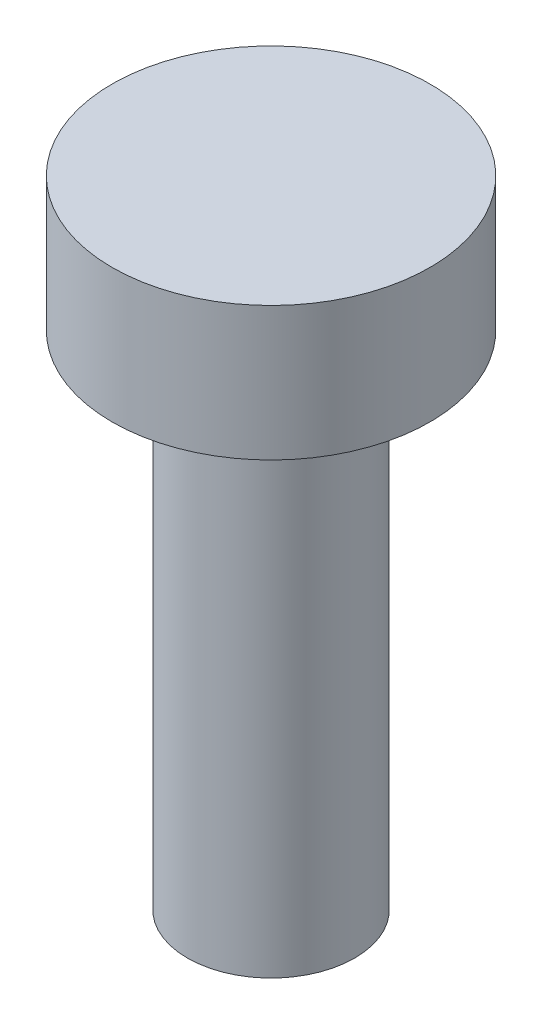
SolidWorks part; units mm, degrees
ref_plane "Front Plane" through (0, 0, 0) normal (0, 0, 1) x (1, 0, 0)
ref_plane "Top Plane" through (0, 0, 0) normal (0, 1, 0) x (1, 0, 0)
ref_plane "Right Plane" through (0, 0, 0) normal (1, 0, 0) x (0, 0, -1)
other "Configuration Table"
sketch "Sketch1" plane through (0, 0, 0) normal (0, 1, 0) x (1, 0, 0)
  circle A0 centre (0, 0) radius 1.9
  dimension "D1" = 3.8
extrude "Head" add sketch "Sketch1" along normal blind 1.6
sketch "Sketch2" plane through (0, 0, 0) normal (0, 1, 0) x (1, 0, 0)
  circle A0 centre (0, 0) radius 1
  dimension "D1" = 2
extrude "Shank" add sketch "Sketch2" along normal blind 6 from offset 6
equation "\"Jar_OD\"= 90  'ASSUMED - Part G fallback - jar outer diameter"
equation "\"Jar_H\"= 120  'ASSUMED - Part G fallback - jar height"
equation "\"Pump_L\"= 45  'ASSUMED - Part G fallback"
equation "\"Pump_W\"= 24  'ASSUMED - Part G fallback"
equation "\"Pump_H\"= 33  'ASSUMED - Part G fallback"
equation "\"Pump_Outlet_OD\"= 7.5  'ASSUMED - Part G fallback"
equation "\"Tube_OD\"= 8  'ASSUMED - Part G fallback"
equation "\"Tube_ID\"= 6  'ASSUMED - Part G fallback"
equation "\"TDS_Body_Dia\"= 12  'ASSUMED - Part G fallback"
equation "\"TDS_Wet_Len\"= 45  'ASSUMED - Part G fallback - length in water"
equation "\"DS_Tube_Dia\"= 6  'ASSUMED - Part G fallback"
equation "\"DS_Tube_Len\"= 50  'ASSUMED - Part G fallback"
equation "\"ORP_Body_Dia\"= 12  'ASSUMED - Part G fallback"
equation "\"ORP_Body_Len\"= 150  'ASSUMED - Part G fallback"
equation "\"ORP_Cap_Dia\"= 16  'ASSUMED - Part G fallback"
equation "\"Turb_W\"= 33  'ASSUMED - Part G fallback - head width"
equation "\"Turb_D\"= 28  'ASSUMED - Part G fallback - head depth"
equation "\"Turb_H\"= 30  'ASSUMED - Part G fallback - head height"
equation "\"Turb_Slot_W\"= 10  'ASSUMED - Part G fallback - slot width"
equation "\"Flow_L\"= 62  'ASSUMED - Part G fallback YF-S201"
equation "\"Flow_W\"= 36  'ASSUMED - Part G fallback"
equation "\"Flow_H\"= 35  'ASSUMED - Part G fallback"
equation "\"Thread_G12_OD\"= 20.955  'ASSUMED - Part G fallback thread G1/2 (major diameter)"
equation "\"Valve_L\"= 75  'ASSUMED - Part G fallback"
equation "\"Valve_W\"= 45  'ASSUMED - Part G fallback"
equation "\"Valve_H\"= 60  'ASSUMED - Part G fallback"
equation "\"Tee_L\"= 40  'ASSUMED - Part G fallback - overall length"
equation "\"Tee_Branch_L\"= 25  'ASSUMED - Part G fallback"
equation "\"Tee_OD\"= 12  'ASSUMED - Part G fallback"
equation "\"LED_Board_L\"= 20  'ASSUMED - Part G fallback"
equation "\"LED_Board_W\"= 20  'ASSUMED - Part G fallback - LED at centre"
equation "\"GUVA_L\"= 20  'ASSUMED - Part G fallback"
equation "\"GUVA_W\"= 12  'ASSUMED - Part G fallback - sensor at centre"
equation "\"Reed_L\"= 27  'ASSUMED - Part G fallback MC-38 half"
equation "\"Reed_W\"= 14  'ASSUMED - Part G fallback"
equation "\"Reed_H\"= 8  'ASSUMED - Part G fallback"
equation "\"ESP_L\"= 51  'ASSUMED - Part G fallback"
equation "\"ESP_W\"= 28  'ASSUMED - Part G fallback"
equation "\"TFT_L\"= 58  'ASSUMED - Part G fallback - board"
equation "\"TFT_W\"= 35  'ASSUMED - Part G fallback - board"
equation "\"TFT_Win_L\"= 35  'ASSUMED - Part G fallback - visible window"
equation "\"TFT_Win_W\"= 28  'ASSUMED - Part G fallback - visible window"
equation "\"Relay_L\"= 50  'ASSUMED - Part G fallback"
equation "\"Relay_W\"= 26  'ASSUMED - Part G fallback"
equation "\"Relay_H\"= 19  'ASSUMED - Part G fallback"
equation "\"Mosfet_L\"= 34  'ASSUMED - Part G fallback"
equation "\"Mosfet_W\"= 17  'ASSUMED - Part G fallback"
equation "\"Mosfet_H\"= 12  'ASSUMED - Part G fallback"
equation "\"TDS_Board_L\"= 42  'ASSUMED - Part G fallback"
equation "\"TDS_Board_W\"= 32  'ASSUMED - Part G fallback"
equation "\"Turb_Board_L\"= 38  'ASSUMED - Part G fallback"
equation "\"Turb_Board_W\"= 28  'ASSUMED - Part G fallback"
equation "\"BNC_Thread_Dia\"= 9.5  'ASSUMED - Part G fallback"
equation "\"Plate_L\"= 420  'ASSUMED - Part G fallback"
equation "\"Plate_W\"= 297  'ASSUMED - Part G fallback"
equation "\"Plate_T\"= 6  'ASSUMED - Part G fallback"
equation "\"Booster_L\"= 150  'ASSUMED - Part G fallback - booster pump"
equation "\"Booster_W\"= 95  'ASSUMED - Part G fallback"
equation "\"Booster_H\"= 100  'ASSUMED - Part G fallback"
equation "\"PTube_OD\"= 6.35  'ASSUMED - Part G fallback - product tube 1/4 inch"
equation "\"Qz_Out\"= 12  'ASSUMED - Part G fallback - quartz channel outside square"
equation "\"Qz_Path\"= 10  'ASSUMED - Part G fallback - quartz channel inside light path"
equation "\"Qz_L\"= 40  'ASSUMED - Part G fallback - quartz channel length"
equation "\"LED860_Dia\"= 5  'ASSUMED - Part G fallback - 860 nm LED"
equation "\"BPW_L\"= 5.4  'ASSUMED - Part G fallback - BPW34"
equation "\"BPW_W\"= 4.3  'ASSUMED - Part G fallback - BPW34"
equation "\"Cart_Dia\"= 50  'ASSUMED - Part G fallback - sediment and pre-carbon cartridges"
equation "\"Cart_L\"= 255  'ASSUMED - Part G fallback"
equation "\"UF_Dia\"= 50  'ASSUMED - Part G fallback - UF cartridge"
equation "\"UF_L\"= 260  'ASSUMED - Part G fallback"
equation "\"RO_Dia\"= 62  'ASSUMED - Part G fallback - RO membrane housing"
equation "\"RO_L\"= 300  'ASSUMED - Part G fallback"
equation "\"UVC_Dia\"= 40  'ASSUMED - Part G fallback - UV-C chamber"
equation "\"UVC_L\"= 300  'ASSUMED - Part G fallback"
equation "\"Tank_W\"= 260  'ASSUMED - Part G fallback - storage tank"
equation "\"Tank_D\"= 160  'ASSUMED - Part G fallback"
equation "\"Tank_H\"= 300  'ASSUMED - Part G fallback"
equation "\"Cab_W\"= 400  'ASSUMED - Part G fallback - purifier cabinet"
equation "\"Cab_D\"= 270  'ASSUMED - Part G fallback"
equation "\"Cab_H\"= 560  'ASSUMED - Part G fallback"
equation "\"ORP_Board_L\"= 40  'ASSUMED - Part G fallback - ORP buffer board"
equation "\"ORP_Board_W\"= 30  'ASSUMED - Part G fallback"
equation "\"Opt_Board_L\"= 50  'ASSUMED - Part G fallback - optical front-end board"
equation "\"Opt_Board_W\"= 40  'ASSUMED - Part G fallback"
equation "\"Buck_L\"= 43  'ASSUMED - Part G fallback - 12 V to 5 V buck module"
equation "\"Buck_W\"= 21  'ASSUMED - Part G fallback"
equation "\"Buck_H\"= 14  'ASSUMED - Part G fallback"
equation "\"BB_L\"= 165  'ASSUMED - Part G fallback - breadboard (As_Built_R3 only)"
equation "\"BB_W\"= 55  'ASSUMED - Part G fallback"
equation "\"BB_H\"= 10  'ASSUMED - Part G fallback"
equation "\"Cuv_W\"= 12.5  'ASSUMED - old R3 cuvette (station suppressed in SS4)"
equation "\"Cuv_D\"= 12.5  'ASSUMED - old R3 cuvette (station suppressed in SS4)"
equation "\"Cuv_H\"= 45  'ASSUMED - old R3 cuvette (station suppressed in SS4)"
equation "\"Probe_Clr\"= 0.3  'DESIGN VALUE - Part C rule 3 - printed probe hole = diameter + 0.3"
equation "\"Label_H\"= 0.6  'DESIGN VALUE - Part D - raised label height"
